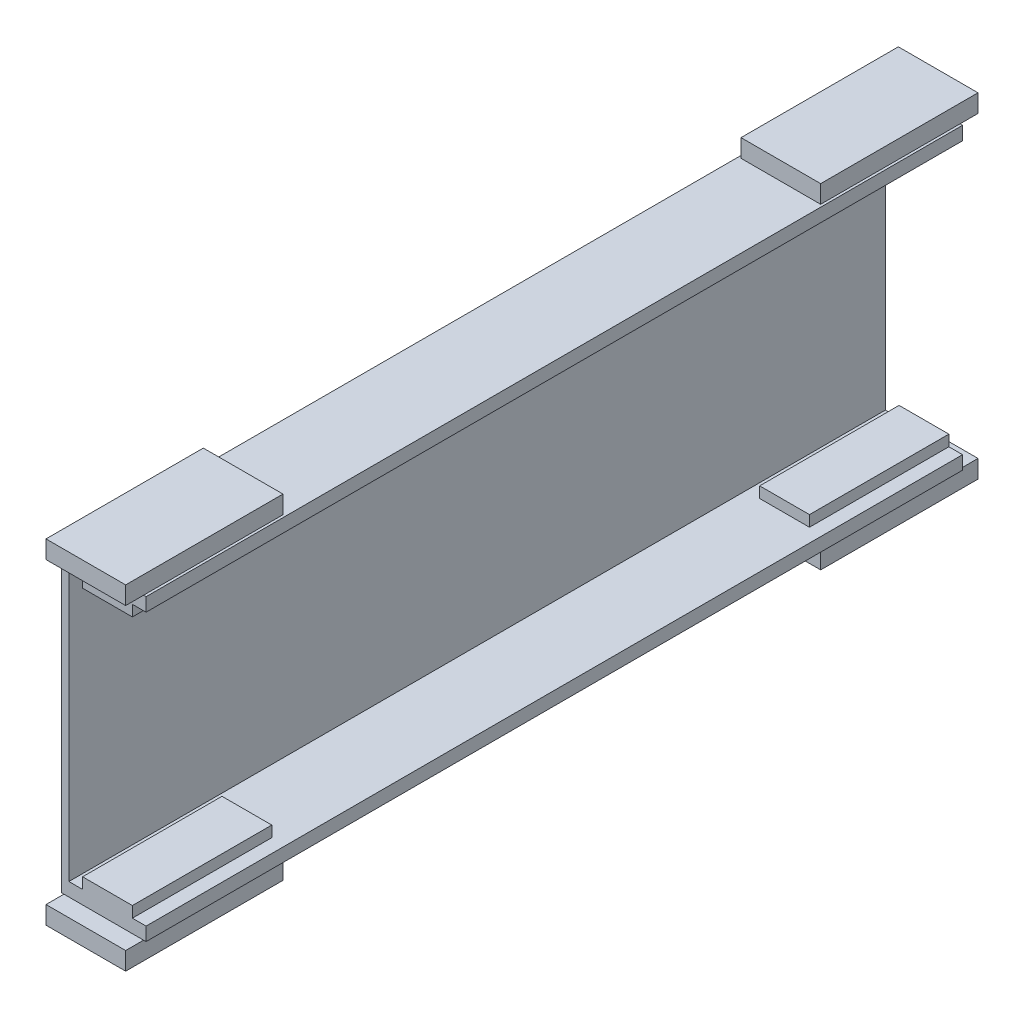
SolidWorks part; units mm, degrees
ref_plane "前视基准面" through (0, 0, 0) normal (0, 0, 1) x (1, 0, 0)
ref_plane "上视基准面" through (0, 0, 0) normal (0, 1, 0) x (1, 0, 0)
ref_plane "右视基准面" through (0, 0, 0) normal (1, 0, 0) x (0, 0, -1)
sketch "草图1" plane through (0, 0, 0) normal (0, 0, 1) x (1, 0, 0)
  line L1 (0, 0) -> (85, 0)
  line L2 (0, 0) -> (0, 300)
  line L3 (0, 300) -> (85, 300)
  line L4 (85, 0) -> (85, 300)
  dimension "D1" = 300
  dimension "D2" = 85
extrude "凸台-拉伸1" add sketch "草图1" along normal blind 820
sketch "草图2" plane through (0, 0, 820) normal (0, 0, 1) x (1, 0, 0)
  line L0 (85, 0) -> (85, 300) construction
  line L1 (7.5, 286.5) -> (85, 286.5)
  line L2 (7.5, 286.5) -> (7.5, 13.5)
  line L3 (7.5, 13.5) -> (85, 13.5)
  line L4 (85, 286.5) -> (85, 13.5)
  line L5 (85, 300) -> (0, 300) construction
  line L6 (0, 300) -> (0, 0) construction
  line L7 (0, 0) -> (85, 0) construction
  dimension "D1" = 13.5
  dimension "D2" = 7.5
  dimension "D3" = 13.5
extrude "切除-拉伸1" cut sketch "草图2" against normal through all
ref_plane "基准面1" through (0, 0, 410) normal (0, 0, -1) x (-1, 0, 0)
ref_plane "基准面2" through (0, 150, 0) normal (0, -1, 0) x (-1, 0, 0)
sketch "草图5" plane through (0, 286.5, 0) normal (0, -1, 0) x (1, 0, 0)
  line L0 (46.25, -1000) -> (46.25, 49000) construction
  line L1 (85, 0) -> (7.5, 0) construction
  line L3 (21.25, 0) -> (71.25, 0)
  line L4 (21.25, 0) -> (21.25, 140)
  line L5 (21.25, 140) -> (71.25, 140)
  line L6 (71.25, 0) -> (71.25, 140)
  point P5 (46.25, 0)
  dimension "D1" = 140
  dimension "D2" = 25
  dimension "D3" = 25
extrude "凸台-拉伸3" add sketch "草图5" along normal blind 11
sketch "草图6" plane through (0, 300, 0) normal (0, 1, 0) x (1, 0, 0)
  line L0 (42.5, -1000) -> (42.5, 49000) construction
  line L1 (85, 0) -> (0, 0) construction
  line L3 (82.5, 18) -> (2.5, 18)
  line L4 (82.5, 18) -> (82.5, -140)
  line L5 (82.5, -140) -> (2.5, -140)
  line L6 (2.5, 18) -> (2.5, -140)
  point P5 (42.5, 0)
  dimension "D1" = 80
  dimension "D2" = 158
  dimension "D3" = 140
extrude "凸台-拉伸4" add sketch "草图6" along normal blind 18
mirror "镜向3" about plane through (0, 150, 0) normal (0, -1, 0) of "凸台-拉伸4", "凸台-拉伸3"
mirror "镜向4" about plane through (0, 0, 410) normal (0, 0, -1) of "镜向3", "凸台-拉伸4", "凸台-拉伸3"
